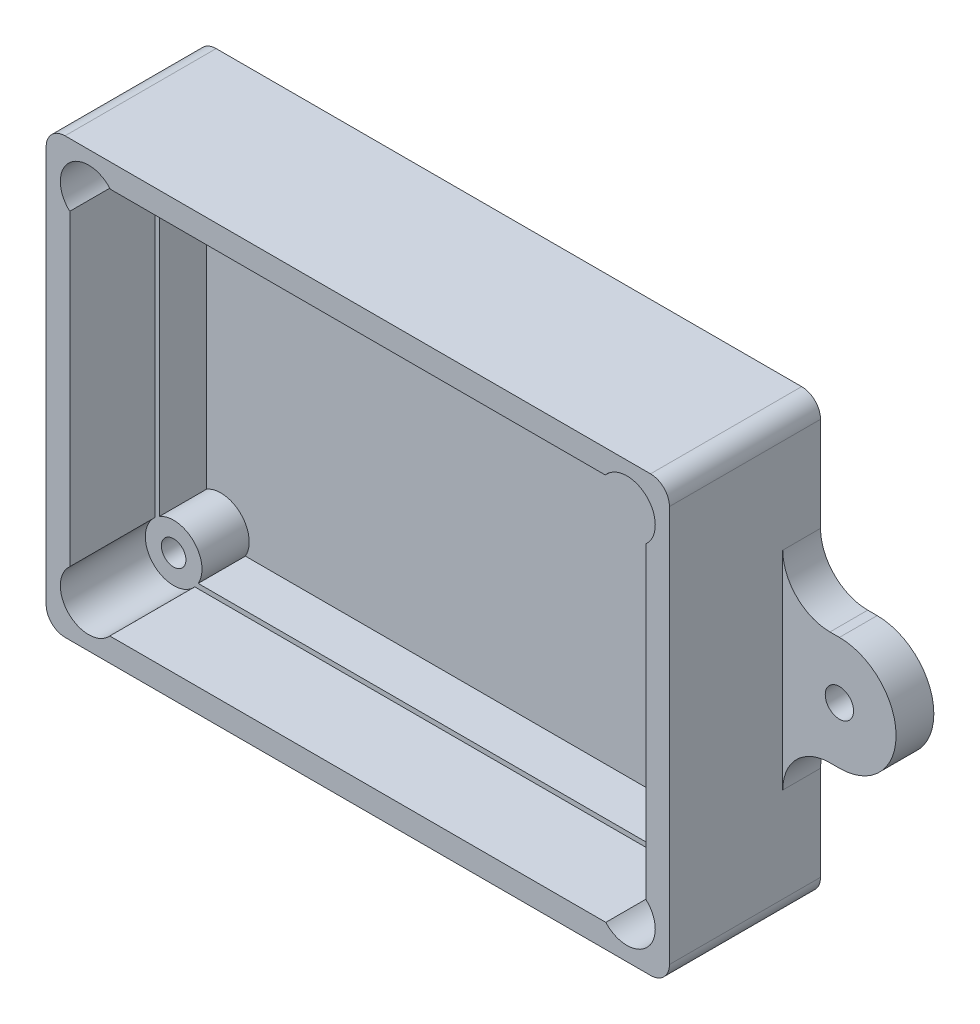
SolidWorks part; units mm, degrees
ref_plane "Front Plane" through (0, 0, 0) normal (0, 0, 1) x (1, 0, 0)
ref_plane "Top Plane" through (0, 0, 0) normal (0, 1, 0) x (1, 0, 0)
ref_plane "Right Plane" through (0, 0, 0) normal (1, 0, 0) x (0, 0, -1)
sketch "Sketch1" plane through (0, 0, 0) normal (0, 0, 1) x (1, 0, 0)
  line L1 (-30, 20) -> (30, 20)
  line L2 (-30, 20) -> (-30, -20)
  line L3 (-30, -20) -> (30, -20)
  line L4 (30, 20) -> (30, -20)
  line L5 (-30, 20) -> (30, -20) construction
  line L6 (-30, -20) -> (30, 20) construction
  circle A0 centre (-28.5, 18.5) radius 1.5
  circle A1 centre (28.5, 18.5) radius 1.5
  circle A2 centre (-28.5, -18.5) radius 1.5
  circle A3 centre (28.5, -18.5) radius 1.5
  circle A4 centre (-28.5, 18.5) radius 1.35
  circle A5 centre (28.5, 18.5) radius 1.3
  circle A6 centre (28.5, -18.5) radius 1.3
  circle A7 centre (-28.5, -18.5) radius 1.3
  circle A8 centre (-28.5, 18.5) radius 3
  circle A9 centre (28.5, 18.5) radius 3
  circle A10 centre (-28.5, -18.5) radius 3
  circle A11 centre (28.5, -18.5) radius 3
  point P0 (0, 0)
extrude "Boss-Extrude1" add sketch "Sketch1" along normal blind 3 contours L2 A8 L1 A0 | L1 A9 L4 A1 | L4 A11 L3 A3 | L3 A10 L2 A2 | A0 L1 L2 | A0 A4 | A1 L4 L1 | A1 A5 | A3 L3 L4 | A3 A6 | A2 L2 L3 | A2 A7
sketch "Sketch2" plane through (0, 0, 0) normal (0, 0, -1) x (-1, 0, 0)
  line L0 (-32, 22) -> (-32, -22)
  line L1 (-30, 20) -> (30, 20)
  line L2 (-30, 20) -> (-30, -20)
  line L3 (-30, -20) -> (30, -20)
  line L4 (30, 20) -> (30, -20)
  line L5 (-32, -22) -> (32, -22)
  line L6 (32, 22) -> (32, -22)
  line L7 (-32, 22) -> (32, 22)
  line M1 (-25.9019, 20) -> (-30, 20)
  line M2 (-30, 20) -> (-30, 15.9019)
  arc M3 (-30, 15.9019) -> (-25.9019, 20) centre (-28.5, 18.5) ccw
  circle M4 centre (-28.5, 18.5) radius 1.3
  dimension "D1" = 2
extrude "Boss-Extrude2" add sketch "Sketch2" along normal blind 2 contours L4 L1 L2 L3 M3 | L7 L0 L5 L6 L1 L4 L3 L2 M2 M1 | M3 M1 M2 M4 | M4
sketch "Sketch3" plane through (0, 0, 0) normal (0, 0, 1) x (1, 0, 0)
  line L1 (32, -22) -> (-32, -22)
  line L2 (32, -22) -> (32, 22)
  line L3 (32, 22) -> (-32, 22)
  line L4 (-32, -22) -> (-32, 22)
  line L5 (30, -20) -> (-30, -20)
  line L6 (30, -20) -> (30, 20)
  line L7 (30, 20) -> (-30, 20)
  line L8 (-30, -20) -> (-30, 20)
extrude "Boss-Extrude3" add sketch "Sketch3" along normal blind 12
sketch "Sketch4" plane through (0, 0, 12) normal (0, 0, 1) x (1, 0, 0)
  line L0 (30.5, -20.5) -> (30.5, 20.5)
  line L1 (30, -20) -> (-30, -20)
  line L2 (30, -20) -> (30, 20)
  line L3 (30, 20) -> (-30, 20)
  line L4 (32, -22) -> (32, 22)
  line L5 (32, 22) -> (-32, 22)
  line L6 (-32, 22) -> (-32, -22)
  line L7 (-32, -22) -> (32, -22)
  line L8 (32, -22) -> (32, 22)
  line L9 (32, 22) -> (-32, 22)
  line L10 (-32, 22) -> (-32, -22)
  line L11 (-32, -22) -> (32, -22)
  line L12 (-30, -20) -> (-30, 20)
  line L13 (30.5, 20.5) -> (-30.5, 20.5)
  line L14 (-30.5, -20.5) -> (-30.5, 20.5)
  line L15 (30.5, -20.5) -> (-30.5, -20.5)
  line M9 (-30, 20) -> (30, 20)
  line M10 (30, 20) -> (30, -20)
  line M11 (30, -20) -> (-30, -20)
  line M12 (-30, -20) -> (-30, 20)
  dimension "D2" = 0.5
  dimension "D1" = 0
extrude "Cut-Extrude1" cut sketch "Sketch4" against normal blind 9 contours L15 L0 L13 L14 M12 M9 M10 M11
sketch "Sketch5" plane through (0, 0, 3) normal (0, 0, 1) x (1, 0, 0)
  circle A0 centre (28.5, -18.5) radius 3
  circle A1 centre (-28.5, -18.5) radius 3
  circle A2 centre (-28.5, 18.5645) radius 3
  circle A3 centre (28.5, 18.5645) radius 3
extrude "Cut-Extrude2" cut sketch "Sketch5" along normal blind 9
sketch "Sketch6" plane through (0, 0, 0) normal (0, 0, 1) x (1, 0, 0)
  line L8 (30, -15.9019) -> (30, 15.9019)
  line L9 (25.9019, 20) -> (-25.9019, 20)
  line L10 (-30, 15.9019) -> (-30, -15.9019)
  line L11 (-25.9019, -20) -> (25.9019, -20)
  line L12 (30, -15.9019) -> (30, 15.9019)
  line L13 (25.9019, 20) -> (-25.9019, 20)
  line L14 (-30, 15.9019) -> (-30, -15.9019)
  line L15 (-25.9019, -20) -> (25.9019, -20)
  arc A8 (30, -15.9019) -> (25.9019, -20) centre (28.5, -18.5) ccw
  arc A9 (25.9019, 20) -> (30, 15.9019) centre (28.5, 18.5) ccw
  arc A10 (-30, 15.9019) -> (-25.9019, 20) centre (-28.5, 18.5) ccw
  arc A11 (-25.9019, -20) -> (-30, -15.9019) centre (-28.5, -18.5) ccw
  arc A12 (30, -15.9019) -> (25.9019, -20) centre (28.5, -18.5) ccw
  arc A13 (25.9019, 20) -> (30, 15.9019) centre (28.5, 18.5) ccw
  arc A14 (-30, 15.9019) -> (-25.9019, 20) centre (-28.5, 18.5) ccw
  arc A15 (-25.9019, -20) -> (-30, -15.9019) centre (-28.5, -18.5) ccw
  dimension "D1" = 0
extrude "Cut-Extrude3" cut sketch "Sketch6" against normal blind 9
sketch "Sketch7" plane through (0, 0, -2) normal (0, 0, -1) x (-1, 0, 0)
  line L4 (32, 22) -> (-32, 22)
  line L5 (-32, 22) -> (-32, -22)
  line L6 (-32, -22) -> (32, -22)
  line L7 (32, -22) -> (32, 22)
  line L8 (32, 22) -> (-32, 22)
  line L9 (-32, 22) -> (-32, -22)
  line L10 (-32, -22) -> (32, -22)
  line L11 (32, -22) -> (32, 22)
  line L16 (33, 23) -> (-33, 23)
  line L17 (-33, 23) -> (-33, -23)
  line L18 (-33, -23) -> (33, -23)
  line L19 (33, -23) -> (33, 23)
  line L20 (33, 23) -> (-33, 23)
  line L21 (-33, 23) -> (-33, -23)
  line L22 (-33, -23) -> (33, -23)
  line L23 (33, -23) -> (33, 23)
  dimension "D1" = 0
  dimension "D2" = 1
extrude "Boss-Extrude4" add sketch "Sketch7" against normal up to surface (14 mm away) up to face at (0, 0, 12)
sketch "Sketch8" plane through (0, 0, -2) normal (0, 0, -1) x (-1, 0, 0)
  line L8 (33, -23) -> (33, 23)
  line L9 (33, 23) -> (-33, 23)
  line L10 (-33, 23) -> (-33, -23)
  line L11 (-33, -23) -> (33, -23)
  line L12 (33, -23) -> (33, 23)
  line L13 (33, 23) -> (-33, 23)
  line L14 (-33, 23) -> (-33, -23)
  line L15 (-33, -23) -> (33, -23)
  dimension "D1" = 0
extrude "Boss-Extrude5" add sketch "Sketch8" along normal blind 2
sketch "Sketch9" plane through (0, 0, -4) normal (0, 0, -1) x (-1, 0, 0)
  line L0 (0, 0) -> (-50000, 0) construction
  line L1 (33, 0) -> (39, 0) construction
  line L2 (-33, 0) -> (-39, 0) construction
  line L3 (33, -23) -> (33, 23) construction
  line L4 (-33, 23) -> (-33, -23) construction
  line L5 (39, 6) -> (-39, 6)
  line L6 (-39, -6) -> (39, -6)
  circle A0 centre (39, 0) radius 1.5
  circle A1 centre (-39, 0) radius 1.5
  circle A2 centre (39, 0) radius 6
  circle A3 centre (-39, 0) radius 6
  line M4 (33, -23) -> (33, 23)
  line M6 (-33, 23) -> (-33, -23)
extrude "Boss-Extrude7" add sketch "Sketch9" against normal blind 4 contours A2 A0 | A2 L5 M4 | A2 L6 M4 | A3 A1 | A3 L5 M6 | A3 L6 M6
fillet "Fillet1" radius 5 4 edges
fillet "Fillet2" radius 2 4 edges at (-33, 23, 4) (33, -23, 4) (-33, -23, 4) (33, 23, 4)
